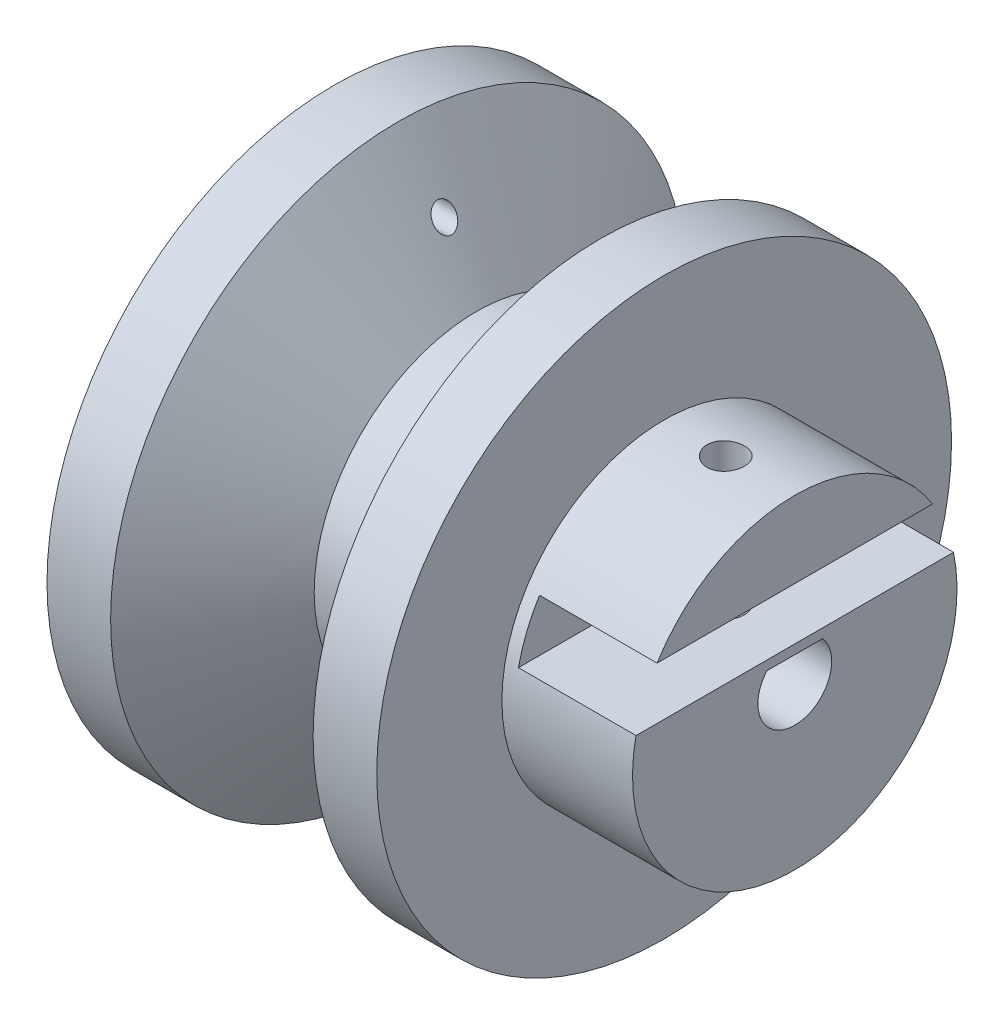
SolidWorks part; units mm, degrees
ref_plane "前基準面" through (0, 0, 0) normal (0, 0, 1) x (1, 0, 0)
ref_plane "上基準面" through (0, 0, 0) normal (0, 1, 0) x (1, 0, 0)
ref_plane "右基準面" through (0, 0, 0) normal (1, 0, 0) x (0, 0, -1)
sketch "草圖1" plane through (0, 0, 0) normal (0, 0, 1) x (1, 0, 0)
  line L0 (0, 0) -> (0, 22)
  line L1 (0, 22) -> (4.87, 22)
  line L2 (4.87, 22) -> (10.87, 12.4189)
  line L3 (10.87, 12.4189) -> (14.37, 12.4189)
  line L4 (14.37, 12.4189) -> (20.37, 22)
  line L5 (20.37, 22) -> (25.24, 22)
  line L6 (25.24, 22) -> (25.24, 12.4189)
  line L7 (25.24, 12.4189) -> (35.24, 12.4189)
  line L8 (35.24, 12.4189) -> (35.24, 0)
  line L9 (-743.1564, 0) -> (36475.4845, 0) construction
  line L10 (0, 0) -> (35.24, 0)
  dimension "D1" = 22
  dimension "D2" = 4.87
  dimension "D3" = 6
  dimension "D4" = 3.5
  dimension "D5" = 6
  dimension "D6" = 4.87
  dimension "D7" = 10
revolve "旋轉1" add sketch "草圖1" angle 360 about L9
ref_plane "平面1" through (0, 12, 0) normal (0, 1, 0) x (1, 0, 0)
sketch "草圖3" plane through (35.24, 0, 0) normal (1, 0, 0) x (0, 0, -1)
  circle A0 centre (0, 0) radius 2.825
  dimension "D1" = 5.65
extrude "除料-伸長2" cut sketch "草圖3" against normal blind 35
sketch "草圖14" plane through (0, 0, 0) normal (-1, 0, 0) x (0, 0, 1)
  circle A0 centre (-0.4353, 17.0039) radius 0.8774
extrude "除料-伸長5" cut sketch "草圖14" against normal blind 12
ref_plane "平面2" through (0, 22, 0) normal (0, 1, 0) x (1, 0, 0)
sketch "草圖16" plane through (35.24, 0, 0) normal (1, 0, 0) x (0, 0, -1)
  line L1 (-2.61, 2.851) -> (2.3989, 2.851)
  line L2 (-2.61, 2.851) -> (-2.61, 1.851)
  line L3 (-2.61, 1.851) -> (2.3989, 1.851)
  line L4 (2.3989, 2.851) -> (2.3989, 1.851)
  dimension "D1" = 1
extrude "填料-伸長2" add sketch "草圖16" against normal blind 30
sketch "草圖19" plane through (35.24, 0, 0) normal (1, 0, 0) x (0, 0, -1)
  line L1 (-0.5637, 2.9297) -> (0.3954, 2.9297)
  line L2 (-0.5637, 2.9297) -> (-0.5637, 2.4182)
  line L3 (-0.5637, 2.4182) -> (0.3954, 2.4182)
  line L4 (0.3954, 2.9297) -> (0.3954, 2.4182)
extrude "填料-伸長3" add sketch "草圖19" against normal blind 30
sketch "草圖24" plane through (35.24, 0, 0) normal (1, 0, 0) x (0, 0, -1)
  line L1 (-12.1511, 6.5651) -> (12.1511, 6.5651)
  line L2 (-12.1511, 6.5651) -> (-12.1511, 2.5651)
  line L3 (-12.1511, 2.5651) -> (12.1511, 2.5651)
  line L4 (12.1511, 6.5651) -> (12.1511, 2.5651)
  line L5 (-12.1511, 6.5651) -> (12.1511, 2.5651) construction
  line L6 (-12.1511, 2.5651) -> (12.1511, 6.5651) construction
  circle A0 centre (0, 0) radius 12.4189 construction
  point P0 (0, 4.5651)
  dimension "D1" = 4
extrude "除料-伸長8" cut sketch "草圖24" against normal blind 9
sketch "草圖25" plane through (0, 22, 0) normal (0, 1, 0) x (1, 0, 0)
  circle A0 centre (29.9567, 0) radius 1.43
  dimension "D1" = 2.86
extrude "除料-伸長9" cut sketch "草圖25" against normal blind 22
